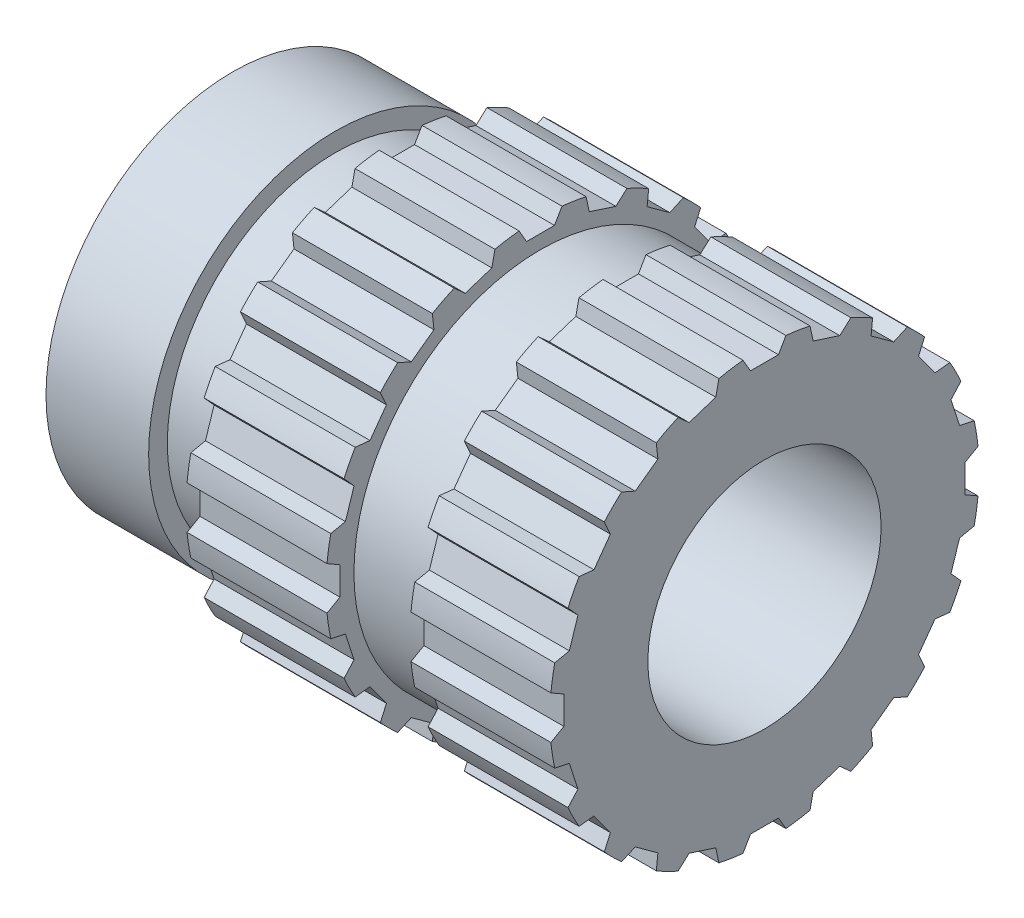
SolidWorks part; units mm, degrees
material "Brass"
ref_plane "Front Plane" through (0, 0, 0) normal (0, 0, 1) x (1, 0, 0)
ref_plane "Top Plane" through (0, 0, 0) normal (0, 1, 0) x (1, 0, 0)
ref_plane "Right Plane" through (0, 0, 0) normal (1, 0, 0) x (0, 0, -1)
sketch "Sketch1" plane through (0, 0, 0) normal (0, 0, 1) x (1, 0, 0)
  line L0 (-2.85, 0) -> (2.85, 0)
  line L1 (2.85, 0) -> (2.85, 2.3)
  line L2 (2.85, 2.3) -> (1.35, 2.3)
  line L3 (1.35, 2.3) -> (1.35, 2)
  line L4 (1.35, 2) -> (0.45, 2)
  line L5 (0.45, 2) -> (0.45, 2.3)
  line L6 (0.45, 2.3) -> (-1.05, 2.3)
  line L7 (-1.05, 2.3) -> (-1.05, 1.8)
  line L9 (-2.85, 2) -> (-2.85, 0)
  line L10 (-1.05, 1.8) -> (-1.75, 1.8)
  line L11 (-1.75, 1.8) -> (-1.75, 2)
  line L12 (-1.75, 2) -> (-2.85, 2)
  point P4 (0, 0)
  dimension "D1" = 2.3
  dimension "D2" = 1.5
  dimension "D3" = 0.9
  dimension "D4" = 5.7
  dimension "D5" = 2
  dimension "D6" = 0.2
  dimension "D7" = 0.7
revolve "Revolve1" add sketch "Sketch1" angle 360 about L0
hole_wizard "M3x0.5 Tapped Hole1" positions "Sketch2" profile "Sketch3" tap size "M3x0.5" standard "ANSI Metric" end condition through all
sketch "Sketch2" plane through (2.85, 0, 0) normal (1, 0, 0) x (0, 0, -1)
  point P0 (0, 0)
sketch "Sketch3" plane through (2.85, 0, 0) normal (0, 1, 0) x (0, 0, -1)
  line L0 (0, 0) -> (0, 5.7)
  line L1 (0, 5.7) -> (1.25, 5.7)
  line L2 (1.25, 5.7) -> (1.25, 0)
  line L5 (1.25, 0) -> (0, 0)
  line L11 (0, -6.35) -> (0, 107.95) construction
  dimension "Thru Tap Drill Dia." = 2.5
  dimension "Thru Tap Drill Depth" = 5.7
cosmetic thread "Hole Thread1" parameters "D2"=3
sketch "Sketch4" plane through (2.85, 0, 0) normal (1, 0, 0) x (0, 0, -1)
  line L0 (0.2299, 2.2885) -> (0.15, 2.15)
  line L1 (0.15, 2.15) -> (-0.15, 2.15)
  line L2 (-0.15, 2.15) -> (-0.2299, 2.2885)
  line L3 (0, 0) -> (0, 2.15) construction
  circle A0 centre (0, 0) radius 2.3 construction
  arc A1 (0.2299, 2.2885) -> (-0.2299, 2.2885) centre (0, 0) ccw
  point P4 (0, 2.15)
  dimension "D1" = 0.3
  dimension "D2" = 0.15
  dimension "D3" = 60
extrude "Cut-Extrude1" cut sketch "Sketch4" against normal up to surface (3.9 mm away) up to face at (-1.05, -1.8, 0)
pattern_circular "CirPattern1" count 20 over 360 about axis through (0, 0, 0) along (1, 0, 0) of "Cut-Extrude1"
